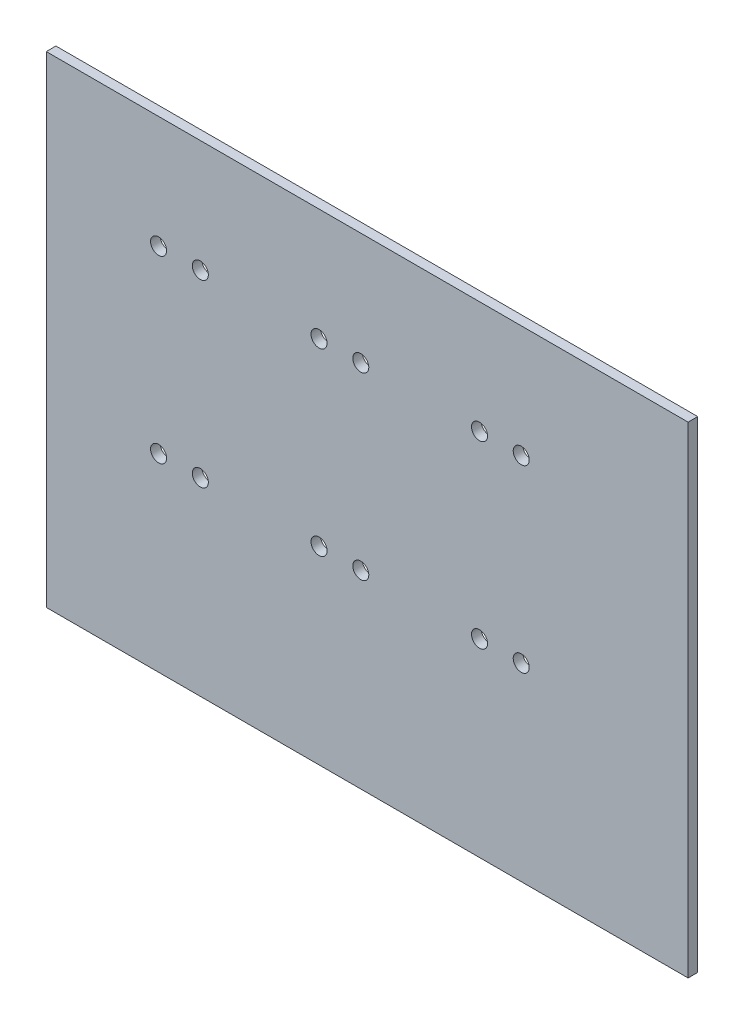
SolidWorks part; units mm, degrees
ref_plane "Přední rovina" through (0, 0, 0) normal (0, 0, 1) x (1, 0, 0)
ref_plane "Horní rovina" through (0, 0, 0) normal (0, 1, 0) x (1, 0, 0)
ref_plane "Pravá rovina" through (0, 0, 0) normal (1, 0, 0) x (0, 0, -1)
sketch "Skica1" plane through (0, 0, 0) normal (0, 0, 1) x (1, 0, 0)
  line L1 (-100, 75) -> (100, 75)
  line L2 (-100, 75) -> (-100, -75)
  line L3 (-100, -75) -> (100, -75)
  line L4 (100, 75) -> (100, -75)
  line L5 (-100, 75) -> (100, -75) construction
  line L6 (-100, -75) -> (100, 75) construction
  point P0 (0, 0)
  dimension "D1" = 200
  dimension "D2" = 150
extrude "Přidat vysunutím1" add sketch "Skica1" along normal blind 3
sketch "Skica2" plane through (0, 0, 3) normal (0, 0, 1) x (1, 0, 0)
  line L2 (-100, 75) -> (-100, -75) construction
  line L3 (-65, 40) -> (-52, 40) construction
  line L4 (-65, 40) -> (-65, -16) construction
  line L5 (-65, -16) -> (-52, -16) construction
  line L6 (-52, 40) -> (-52, -16) construction
  line L7 (-15, 40) -> (-2, 40) construction
  line L8 (-15, 40) -> (-15, -16) construction
  line L9 (-15, -16) -> (-2, -16) construction
  line L10 (-2, 40) -> (-2, -16) construction
  line L11 (35, 40) -> (48, 40) construction
  line L12 (35, 40) -> (35, -16) construction
  line L13 (35, -16) -> (48, -16) construction
  line L14 (48, 40) -> (48, -16) construction
  line L15 (100, 75) -> (-100, 75) construction
  circle A4 centre (-65, 40) radius 2.5
  circle A5 centre (-52, 40) radius 2.5
  circle A6 centre (-52, -16) radius 2.5
  circle A7 centre (-65, -16) radius 2.5
  circle A8 centre (-15, -16) radius 2.5
  circle A9 centre (-2, -16) radius 2.5
  circle A10 centre (-2, 40) radius 2.5
  circle A11 centre (-15, 40) radius 2.5
  circle A12 centre (35, 40) radius 2.5
  circle A13 centre (48, 40) radius 2.5
  circle A14 centre (48, -16) radius 2.5
  circle A15 centre (35, -16) radius 2.5
  dimension "D1" = 56
  dimension "D4" = 13
  dimension "D6" = 13
  dimension "D9" = 50
  dimension "D13" = 5
  dimension "D14" = 5
  dimension "D15" = 5
  dimension "D16" = 5
  dimension "D17" = 5
  dimension "D18" = 5
  dimension "D19" = 5
  dimension "D20" = 5
  dimension "D21" = 5
  dimension "D22" = 5
  dimension "D23" = 5
  dimension "D24" = 5
  dimension "D2" = 13
  dimension "D3" = 56
  dimension "D5" = 56
  dimension "D7" = 35
  dimension "D8" = 35
  dimension "D10" = 35
  dimension "D11" = 50
  dimension "D12" = 35
extrude "Odebrat vysunutím1" cut sketch "Skica2" against normal through all
